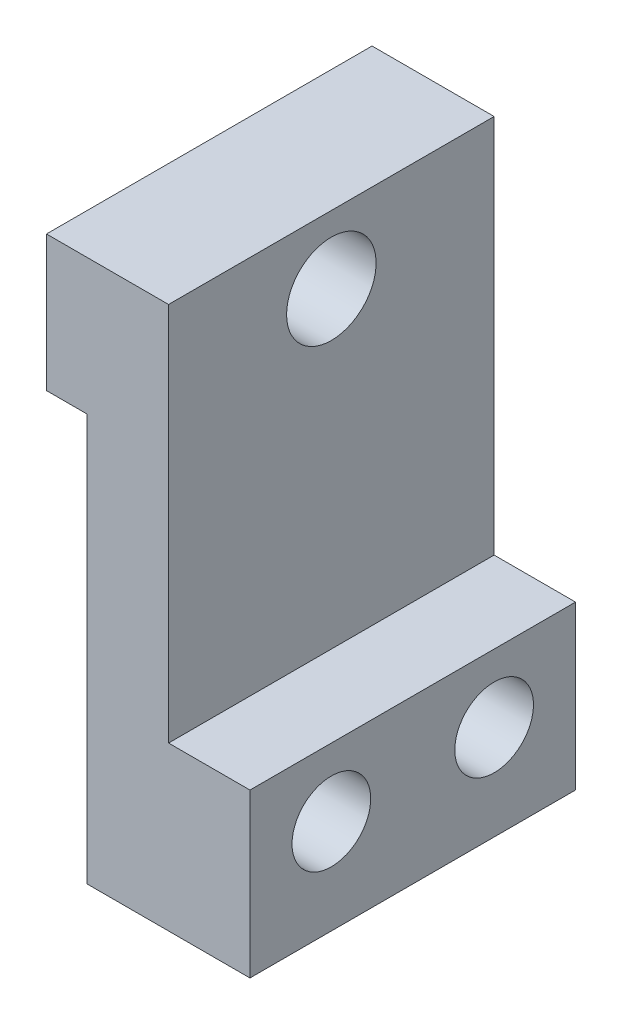
SolidWorks part; units mm, degrees
ref_plane "Front Plane" through (0, 0, 0) normal (0, 0, 1) x (1, 0, 0)
ref_plane "Top Plane" through (0, 0, 0) normal (0, 1, 0) x (1, 0, 0)
ref_plane "Right Plane" through (0, 0, 0) normal (1, 0, 0) x (0, 0, -1)
sketch "Sketch1" plane through (0, 0, 0) normal (0, 0, 1) x (1, 0, 0)
  line L0 (0, 21.3158) -> (0, -26.0526) construction
  line L1 (0, -6.8684) -> (-6, -6.8684)
  line L2 (-6, -6.8684) -> (-6, 8.1316)
  line L3 (-6, 8.1316) -> (-7.5, 8.1316)
  line L4 (-7.5, 8.1316) -> (-7.5, 13.1316)
  line L5 (-7.5, 13.1316) -> (-3, 13.1316)
  line L6 (-3, 13.1316) -> (-3, -0.8684)
  line L7 (-3, -0.8684) -> (0, -0.8684)
  line L8 (0, -0.8684) -> (0, -6.8684)
  dimension "D1" = 6
  dimension "D2" = 5
  dimension "D3" = 20
  dimension "D4" = 3
  dimension "D5" = 6
  dimension "D6" = 1.5
extrude "Boss-Extrude1" add sketch "Sketch1" along normal blind 12
hole_wizard "M2.5 Clearance Hole1" positions "Sketch3" profile "Sketch4" hole size "M2.5" standard "ANSI Metric" end condition through all
sketch "Sketch3" plane through (-6, 0, 0) normal (-1, 0, 0) x (0, 0, 1)
  line L0 (12, -6.8684) -> (0, -6.8684) construction
  line L1 (0, 8.1316) -> (0, -6.8684) construction
  point P0 (3, -3.3684)
  point P2 (9, -3.3684)
  dimension "D1" = 6
  dimension "D2" = 3.5
  dimension "D3" = 3
sketch "Sketch4" plane through (-6, -3.3684, 3) normal (0, 1, 0) x (0, 0, 1)
  line L0 (0, 0) -> (0, 6)
  line L1 (0, 6) -> (1.45, 6)
  line L2 (1.45, 6) -> (1.45, 0)
  line L5 (1.45, 0) -> (0, 0)
  line L11 (0, -6.35) -> (0, 107.95) construction
  dimension "Thru Hole Dia." = 2.9
  dimension "Thru Hole Depth" = 6
hole_wizard "Tap Drill for M4x0.7 Tap1" positions "Sketch5" profile "Sketch6" hole size "M4x0.7" standard "ANSI Metric" end condition through all
sketch "Sketch5" plane through (-7.5, 0, 0) normal (-1, 0, 0) x (0, 0, 1)
  line L0 (12, -6.8684) -> (0, -6.8684) construction
  line L1 (0, 13.1316) -> (0, 8.1316) construction
  point P0 (6, 10.6316)
  dimension "D1" = 17.5
  dimension "D2" = 6
sketch "Sketch6" plane through (-7.5, 10.6316, 6) normal (0, 1, 0) x (0, 0, 1)
  line L0 (0, 0) -> (0, 7.5)
  line L1 (0, 7.5) -> (1.65, 7.5)
  line L2 (1.65, 7.5) -> (1.65, 0)
  line L5 (1.65, 0) -> (0, 0)
  line L11 (0, -6.35) -> (0, 107.95) construction
  dimension "Thru Hole Dia." = 3.3
  dimension "Thru Hole Depth" = 7.5
